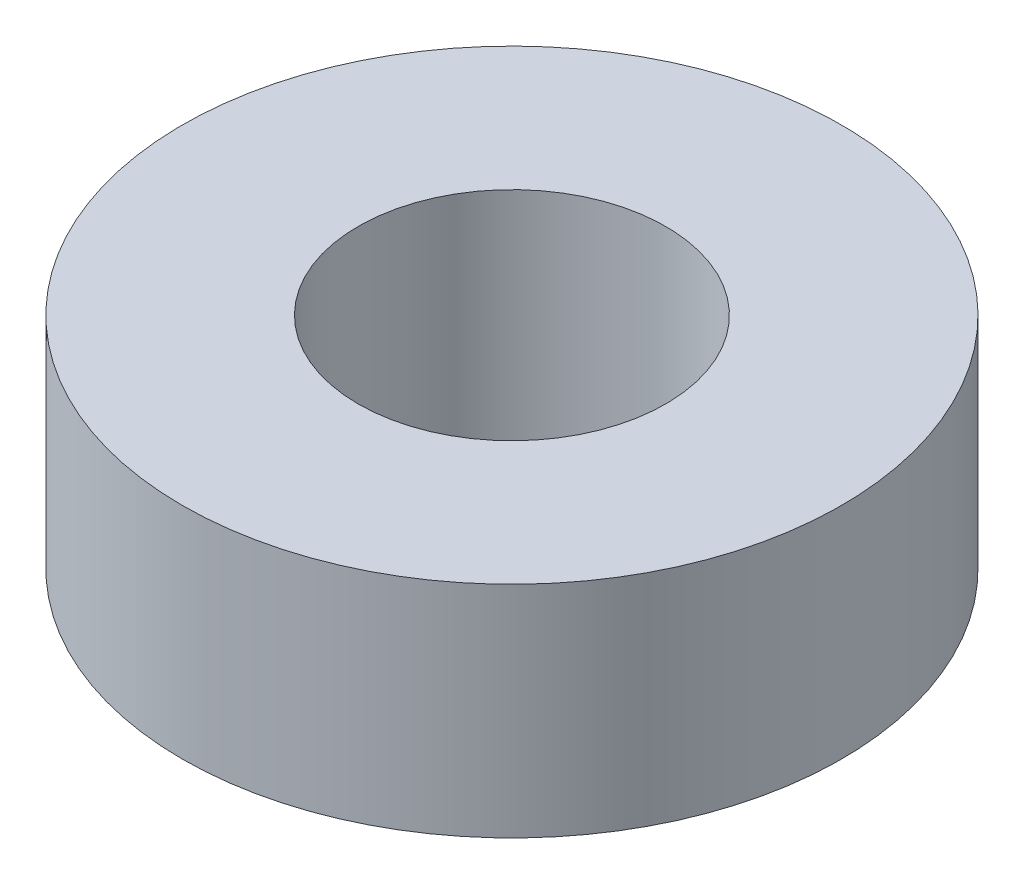
SolidWorks part; units mm, degrees
ref_plane "Front Plane" through (0, 0, 0) normal (0, 0, 1) x (1, 0, 0)
ref_plane "Top Plane" through (0, 0, 0) normal (0, 1, 0) x (1, 0, 0)
ref_plane "Right Plane" through (0, 0, 0) normal (1, 0, 0) x (0, 0, -1)
sketch "Sketch1" plane through (0, 0, 0) normal (0, 1, 0) x (1, 0, 0)
  circle A0 centre (0, 0) radius 15
  circle A1 centre (0, 0) radius 7
  dimension "D1" = 30
  dimension "D2" = 8
extrude "Boss-Extrude1" add sketch "Sketch1" along normal blind 10
